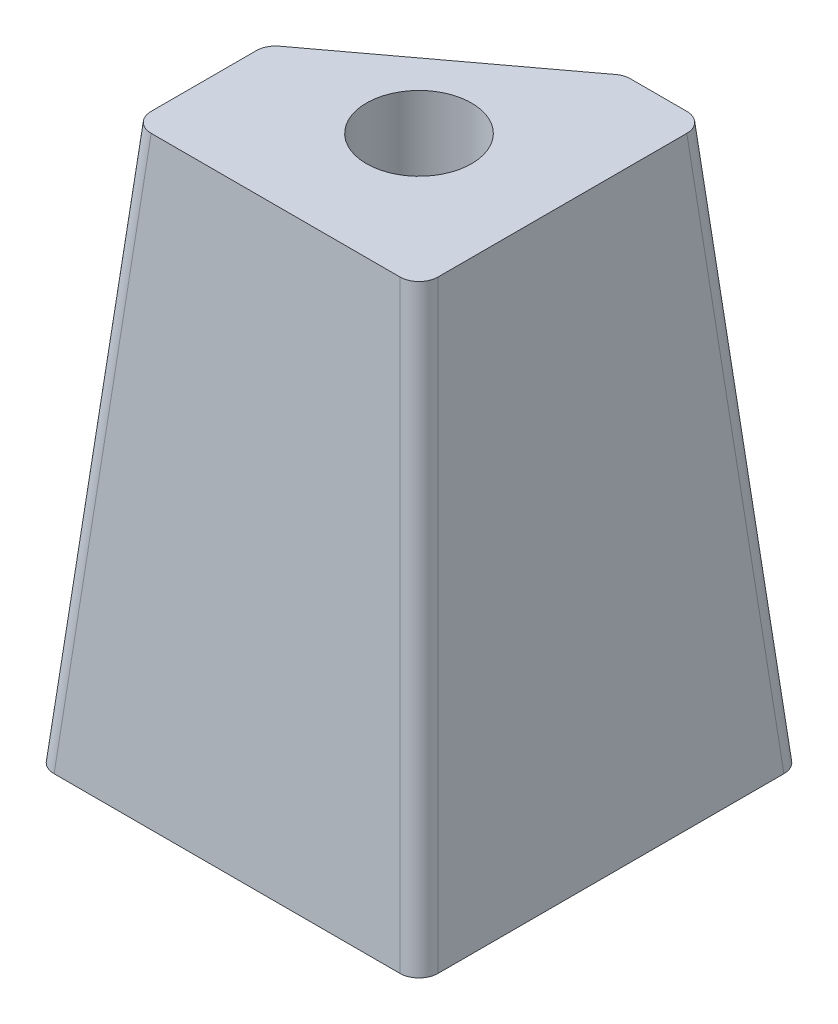
SolidWorks part; units mm, degrees
ref_plane "Front Plane" through (0, 0, 0) normal (0, 0, 1) x (1, 0, 0)
ref_plane "Top Plane" through (0, 0, 0) normal (0, 1, 0) x (1, 0, 0)
ref_plane "Right Plane" through (0, 0, 0) normal (1, 0, 0) x (0, 0, -1)
sketch "Sketch1" plane through (0, 0, 0) normal (0, 1, 0) x (1, 0, 0)
  line L0 (-4.5796, -0.2013) -> (6.1532, 7.7987)
  line L1 (6.1532, 7.7987) -> (10.4204, 7.7987)
  line L2 (10.4204, 7.7987) -> (10.4204, -7.2013)
  line L3 (10.4204, -7.2013) -> (-4.5796, -7.2013)
  line L4 (-4.5796, -7.2013) -> (-4.5796, -0.2013)
  dimension "D1" = 15
  dimension "D2" = 15
  dimension "D4" = 7
  dimension "D5" = 126.7
extrude "Boss-Extrude1" add sketch "Sketch1" along normal blind 29
sketch "Sketch2" plane through (0, 0, 0) normal (0, -1, 0) x (1, 0, 0)
  line L0 (-4.5796, 0.2013) -> (-4.5796, 7.2013) construction
  line L1 (10.4204, 7.2013) -> (10.4204, -7.7987) construction
  line L2 (-4.5796, 7.2013) -> (10.4204, 7.2013) construction
  circle A0 centre (-0.5796, 2.2013) radius 1.5
  circle A1 centre (7.4204, 2.2013) radius 2
  dimension "D1" = 3
  dimension "D3" = 4
  dimension "D2" = 4
  dimension "D4" = 3
  dimension "D5" = 5
  dimension "D6" = 5
extrude "Cut-Extrude1" cut sketch "Sketch2" against normal blind 10
sketch "Sketch3" plane through (0, 29, 0) normal (0, 1, 0) x (1, 0, 0)
  line L0 (10.4204, -7.2013) -> (10.4204, 7.7987) construction
  line L1 (-4.5796, -7.2013) -> (10.4204, -7.2013) construction
  circle A0 centre (3.4204, -0.2013) radius 2.75
  dimension "D1" = 5.5
  dimension "D2" = 7
  dimension "D3" = 7
extrude "Cut-Extrude2" cut sketch "Sketch3" against normal blind 6
draft "Draft1" type of draft neutral plane draft angle 5 faces to draft 5 face at (8.2868, 14.5, -7.7987) face at (10.4204, 14.5, -0.2987) face at (2.9204, 14.5, 7.2013) face at (-4.5796, 14.5, 3.7013) face at (0.7868, 14.5, -3.7987) neutral plane through (0, 29, 0) neutral plane normal (0, 1, 0) parameters "D1"=5
fillet "Fillet1" radius 1 5 edges at (5.7324, 14.5, -9.0673) (-5.8482, 14.5, -0.4353) (11.6889, 14.5, -9.0673) (11.6889, 14.5, 8.4699) (-5.8482, 14.5, 8.4699)
